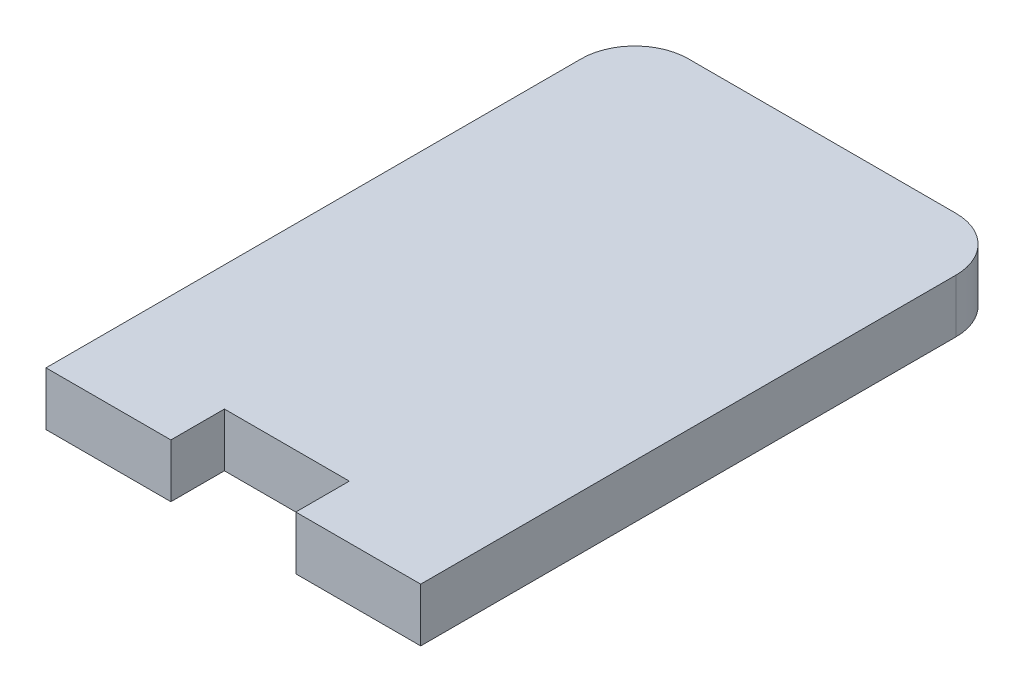
SolidWorks part; units mm, degrees
ref_plane "Front Plane" through (0, 0, 0) normal (0, 0, 1) x (1, 0, 0)
ref_plane "Top Plane" through (0, 0, 0) normal (0, 1, 0) x (1, 0, 0)
ref_plane "Right Plane" through (0, 0, 0) normal (1, 0, 0) x (0, 0, -1)
sketch "Sketch2" plane through (0, 0, 0) normal (0, 1, 0) x (1, 0, 0)
  line L1 (-10.5, -16.5) -> (10.5, -16.5)
  line L2 (-10.5, -16.5) -> (-10.5, 16.5)
  line L3 (-10.5, 16.5) -> (10.5, 16.5)
  line L4 (10.5, -16.5) -> (10.5, 16.5)
  line L5 (-10.5, -16.5) -> (10.5, 16.5) construction
  line L6 (-10.5, 16.5) -> (10.5, -16.5) construction
  point P0 (0, 0)
  dimension "D1" = 21
  dimension "D2" = 33
extrude "Boss-Extrude1" add sketch "Sketch2" along normal blind 3
sketch "Sketch4" plane through (0, 3, 0) normal (0, 1, 0) x (1, 0, 0)
  line L0 (-10.5, -16.5) -> (10.5, -16.5) construction
  line L1 (-3.5, -16.5) -> (3.5, -16.5)
  line L2 (-3.5, -16.5) -> (-3.5, -13.5)
  line L3 (-3.5, -13.5) -> (3.5, -13.5)
  line L4 (3.5, -16.5) -> (3.5, -13.5)
  line L5 (-10.5, 16.5) -> (-10.5, -16.5) construction
  dimension "D1" = 3
  dimension "D2" = 7
  dimension "D3" = 7
extrude "Cut-Extrude2" cut sketch "Sketch4" against normal blind 3
fillet "Fillet1" radius 3 1 edges at (-10.5, 1.5, -16.5)
fillet "Fillet2" radius 3 1 edges at (10.5, 1.5, -16.5)
